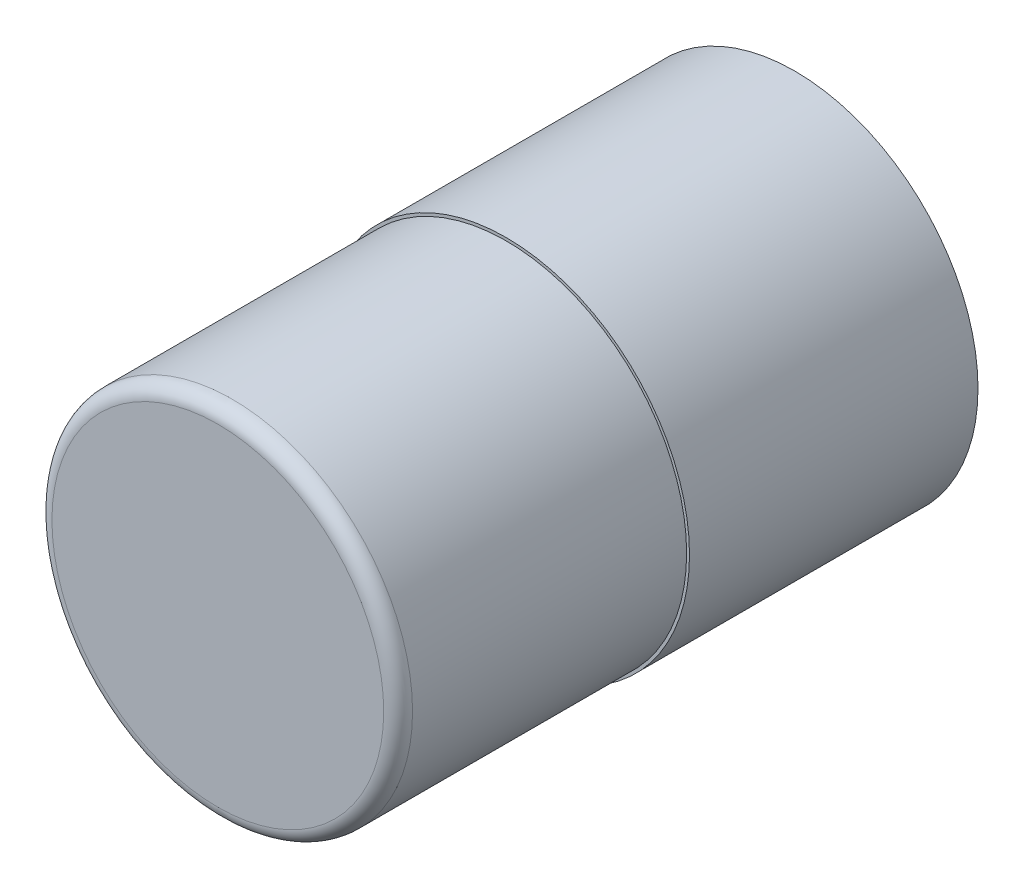
SolidWorks part; units mm, degrees
ref_plane "Front Plane" through (0, 0, 0) normal (0, 0, 1) x (1, 0, 0)
ref_plane "Top Plane" through (0, 0, 0) normal (0, 1, 0) x (1, 0, 0)
ref_plane "Right Plane" through (0, 0, 0) normal (1, 0, 0) x (0, 0, -1)
sketch "Sketch1" plane through (0, 0, 0) normal (0, 0, 1) x (1, 0, 0)
  circle A0 centre (0, 0) radius 6.35
  circle A1 centre (0, 0) radius 2.8
  dimension "D1" = 5.6
  dimension "D2" = 12.7
extrude "Boss-Extrude2" add sketch "Sketch1" along normal blind 10
sketch "Sketch2" plane through (0, 0, 10) normal (0, 0, 1) x (1, 0, 0)
  circle A0 centre (0, 0) radius 6.35
extrude "Boss-Extrude3" add sketch "Sketch2" along normal blind 10
sketch "Sketch3" plane through (0, 0, 20) normal (0, 0, 1) x (1, 0, 0)
  circle A0 centre (0, 0) radius 6.25
  circle A1 centre (0, 0) radius 6.25
  circle A2 centre (0, 0) radius 6.35 construction
  circle M1 centre (0, 0) radius 6.35
  dimension "D1" = 12.5
  dimension "D2" = 0.1
extrude "Cut-Extrude1" cut sketch "Sketch3" against normal blind 10 contours A0 M1
fillet "Fillet1" radius 0.5 1 edges at (6.25, 0, 20)
